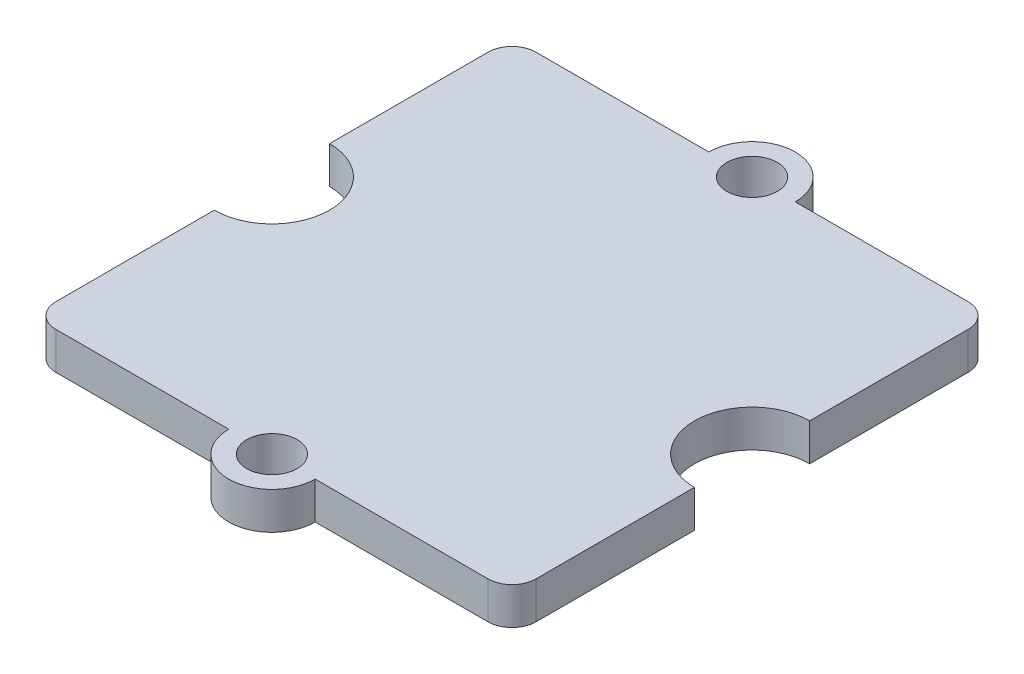
SolidWorks part; units mm, degrees
ref_plane "Plan de face" through (0, 0, 0) normal (0, 0, 1) x (1, 0, 0)
ref_plane "Plan de dessus" through (0, 0, 0) normal (0, 1, 0) x (1, 0, 0)
ref_plane "Plan de droite" through (0, 0, 0) normal (1, 0, 0) x (0, 0, -1)
sketch "Esquisse1" plane through (0, 0, 0) normal (0, 1, 0) x (1, 0, 0)
  line L0 (10, 20) -> (10, 0) construction
  line L1 (1, 0) -> (8.2, 0)
  line L2 (0, 1) -> (0, 7.6)
  line L3 (1, 20) -> (8.2, 20)
  line L4 (20, 1) -> (20, 7.6)
  line L5 (10, 21.8) -> (14.1998, 21.8) construction
  line L6 (10, -1.8) -> (13.7569, -1.8) construction
  line L7 (11.8, 20) -> (19, 20)
  line L8 (11.8, 0) -> (19, 0)
  line L9 (0, 12.4) -> (0, 19)
  line L10 (20, 12.4) -> (20, 19)
  arc A0 (11.8, 20) -> (8.2, 20) centre (10, 20) ccw
  arc A1 (8.2, 0) -> (11.8, 0) centre (10, 0) ccw
  circle A2 centre (10, 0) radius 1.05
  circle A3 centre (10, 20) radius 1.05
  arc A4 (0, 7.6) -> (0, 12.4) centre (0, 10) ccw
  arc A5 (20, 12.4) -> (20, 7.6) centre (20, 10) ccw
  arc A6 (1, 0) -> (0, 1) centre (1, 1) cw
  arc A7 (19, 0) -> (20, 1) centre (19, 1) ccw
  arc A8 (19, 20) -> (20, 19) centre (19, 19) cw
  arc A9 (0, 19) -> (1, 20) centre (1, 19) cw
  point P25 (0, 0)
  point P28 (20, 0)
  point P33 (0, 20)
  dimension "D4" = 2.1
  dimension "D5" = 2.1
  dimension "D6" = 4.8
  dimension "D7" = 4.8
  dimension "D8" = 1
  dimension "D1" = 20
  dimension "D2" = 20
  dimension "D3" = 23.6
extrude "Boss.-Extru.1" add sketch "Esquisse1" along normal blind 1.55
